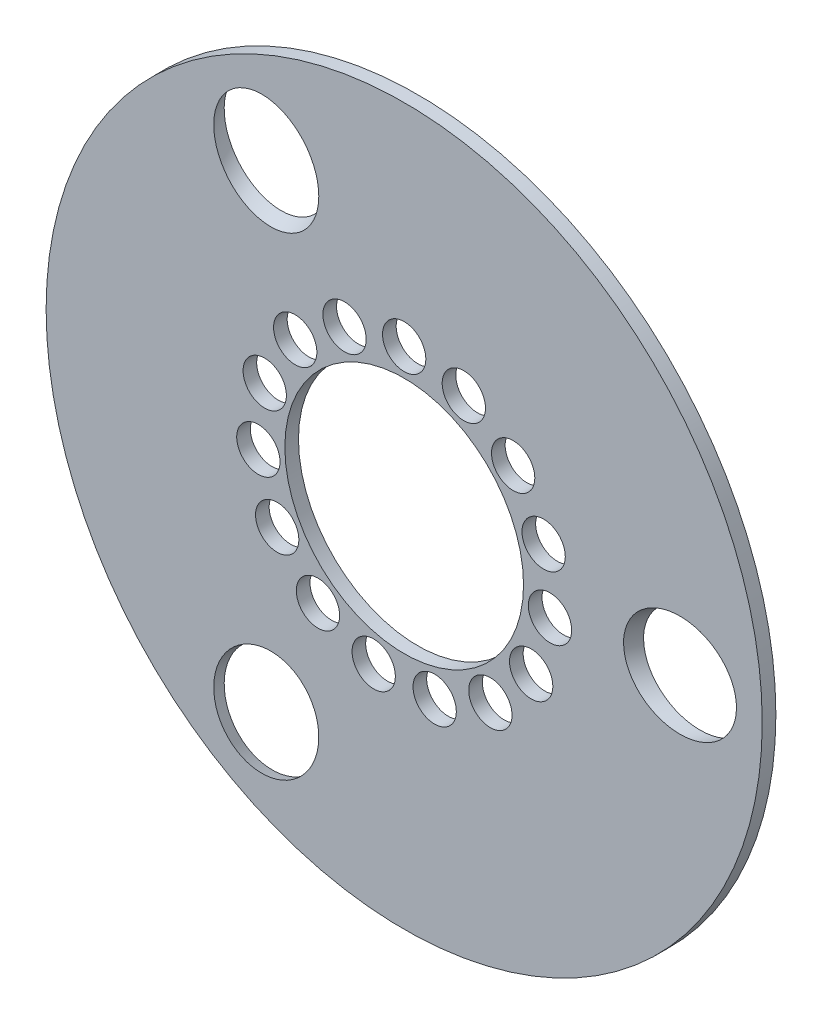
SolidWorks part; units mm, degrees
ref_plane "Front Plane" through (0, 0, 0) normal (0, 0, 1) x (1, 0, 0)
ref_plane "Top Plane" through (0, 0, 0) normal (0, 1, 0) x (1, 0, 0)
ref_plane "Right Plane" through (0, 0, 0) normal (1, 0, 0) x (0, 0, -1)
sketch "Sketch1" plane through (0, 0, 0) normal (0, 0, 1) x (1, 0, 0)
  circle A0 centre (0, 0) radius 52.5
  dimension "D1" = 105
extrude "Boss-Extrude2" add sketch "Sketch1" along normal blind 2
sketch "Sketch2" plane through (0, 0, 0) normal (0, 0, 1) x (1, 0, 0)
  line L0 (0, 49.1023) -> (0, -45.1008) construction
  line L1 (136.3087, 0) -> (-63.6913, 0) construction
  line L2 (-56.6886, 100) -> (-56.6886, -100) construction
  line L3 (-68.7048, 120) -> (123.4995, 9.0308) construction
  line L4 (-68.7048, -120) -> (123.4995, -9.0308) construction
  dimension "D1" = 200
  dimension "D2" = 200
  dimension "D3" = 60
  dimension "D4" = 120
ref_plane "Plane1" through (-10.1249, 0, 21.713) normal (-0.4226, 0, 0.9063) x (0, -1, 0)
sketch "Sketch4" plane through (0, 0, 0) normal (0, 0, 1) x (1, 0, 0)
  line L0 (0, 45.4345) -> (0, -41.0682) construction
  line L1 (0, 49.1023) -> (0, -45.1008) construction
  circle A0 centre (0, 21.5) radius 3.175
  circle A1 centre (8.7448, 19.6412) radius 3.175
  circle A2 centre (15.9776, 14.3863) radius 3.175
  circle A3 centre (20.4477, 6.6439) radius 3.175
  circle A4 centre (21.3822, -2.2474) radius 3.175
  circle A5 centre (18.6195, -10.75) radius 3.175
  circle A6 centre (12.6374, -17.3939) radius 3.175
  circle A7 centre (4.4701, -21.0302) radius 3.175
  circle A8 centre (-4.4701, -21.0302) radius 3.175
  circle A9 centre (-12.6374, -17.3939) radius 3.175
  circle A10 centre (-18.6195, -10.75) radius 3.175
  circle A11 centre (-21.3822, -2.2474) radius 3.175
  circle A12 centre (-20.4477, 6.6439) radius 3.175
  circle A13 centre (-15.9776, 14.3863) radius 3.175
  circle A14 centre (-8.7448, 19.6412) radius 3.175
  point P38 (0, 0)
  dimension "D1" = 6.35
  dimension "D2" = 21.5
  dimension "D3" = 15
extrude "Cut-Extrude2" cut sketch "Sketch4" along normal blind 2
sketch "Sketch5" plane through (-10.1249, 0, 21.713) normal (-0.4226, 0, 0.9063) x (0, -1, 0)
  line L0 (0, 61.2511) -> (0, -65.9896) construction
  circle A0 centre (0, 37.5) radius 7.5
  dimension "D1" = 15
  dimension "D2" = 37.5
extrude "Cut-Extrude3" cut sketch "Sketch5" against normal blind 102
ref_plane "Plane2" through (6.2129, 10.761, 26.6471) normal (-0.2113, -0.366, -0.9063) x (0.866, -0.5, 0)
sketch "Sketch6" plane through (6.2129, 10.761, 26.6471) normal (-0.2113, -0.366, -0.9063) x (0.866, -0.5, 0)
  line L0 (0, 187.2491) -> (0, -135.2) construction
  circle A0 centre (0, 37.5) radius 7.5
  dimension "D1" = 15
  dimension "D2" = 37.5
extrude "Cut-Extrude4" cut sketch "Sketch6" along normal blind 102
ref_plane "Plane3" through (6.2129, -10.761, 26.6471) normal (0.2113, -0.366, 0.9063) x (0.866, 0.5, 0)
sketch "Sketch7" plane through (6.2129, -10.761, 26.6471) normal (0.2113, -0.366, 0.9063) x (0.866, 0.5, 0)
  line L0 (0, 203.3976) -> (0, -134.1581) construction
  circle A0 centre (0, 37.5) radius 7.5
  dimension "D1" = 15
  dimension "D2" = 37.5
extrude "Cut-Extrude5" cut sketch "Sketch7" against normal blind 102
sketch "Sketch8" plane through (0, 0, 0) normal (0, 0, 1) x (1, 0, 0)
  circle A0 centre (0, 0) radius 17.5
  dimension "D1" = 35
extrude "Cut-Extrude6" cut sketch "Sketch8" along normal blind 10
